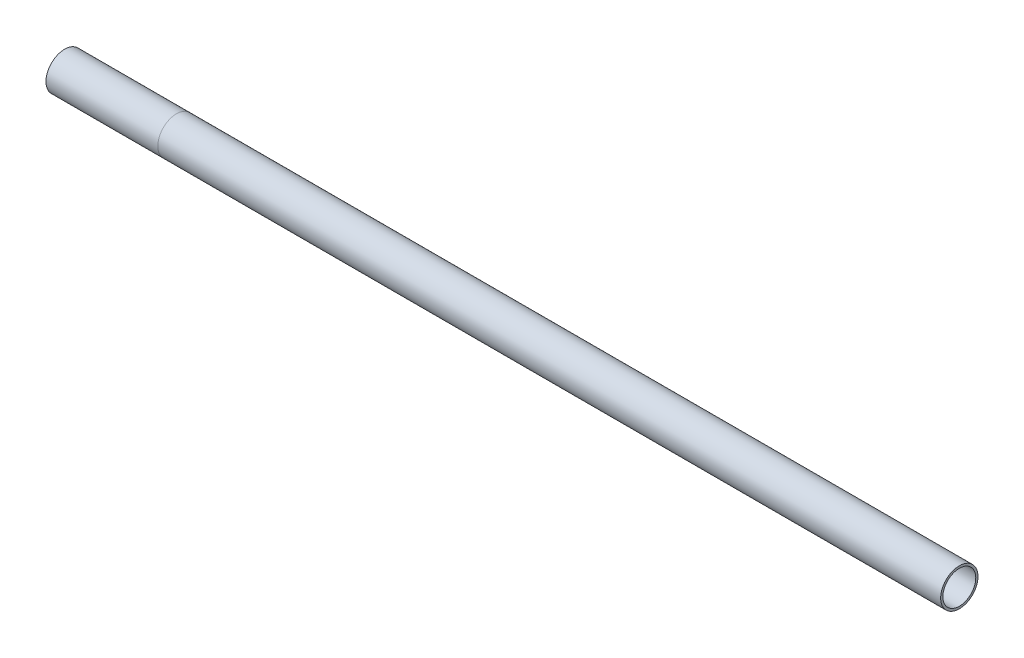
SolidWorks part; units mm, degrees
ref_plane "Front Plane" through (0, 0, 0) normal (0, 0, 1) x (1, 0, 0)
ref_plane "Top Plane" through (0, 0, 0) normal (0, 1, 0) x (1, 0, 0)
ref_plane "Right Plane" through (0, 0, 0) normal (1, 0, 0) x (0, 0, -1)
sketch "Sketch1" plane through (0, 0, 0) normal (1, 0, 0) x (0, 0, -1)
  circle A0 centre (-2.7196, 5.1842) radius 7.35
  circle A1 centre (-2.7196, 5.1842) radius 8.35
  dimension "D1" = 14.7
  dimension "D2" = 1
sketch "Sketch2" plane through (0, 0, 0) normal (0, 0, 1) x (1, 0, 0)
  line L0 (0, 5.1842) -> (50, 5.1842)
  line L1 (0, -2.1658) -> (0, 12.5342) construction
  line L6 (50, 5.1842) -> (400, 5.1842)
  dimension "D1" = 350
  dimension "D5" = 50
sweep "Sweep1" add profiles "Sketch1" path "Sketch2"
